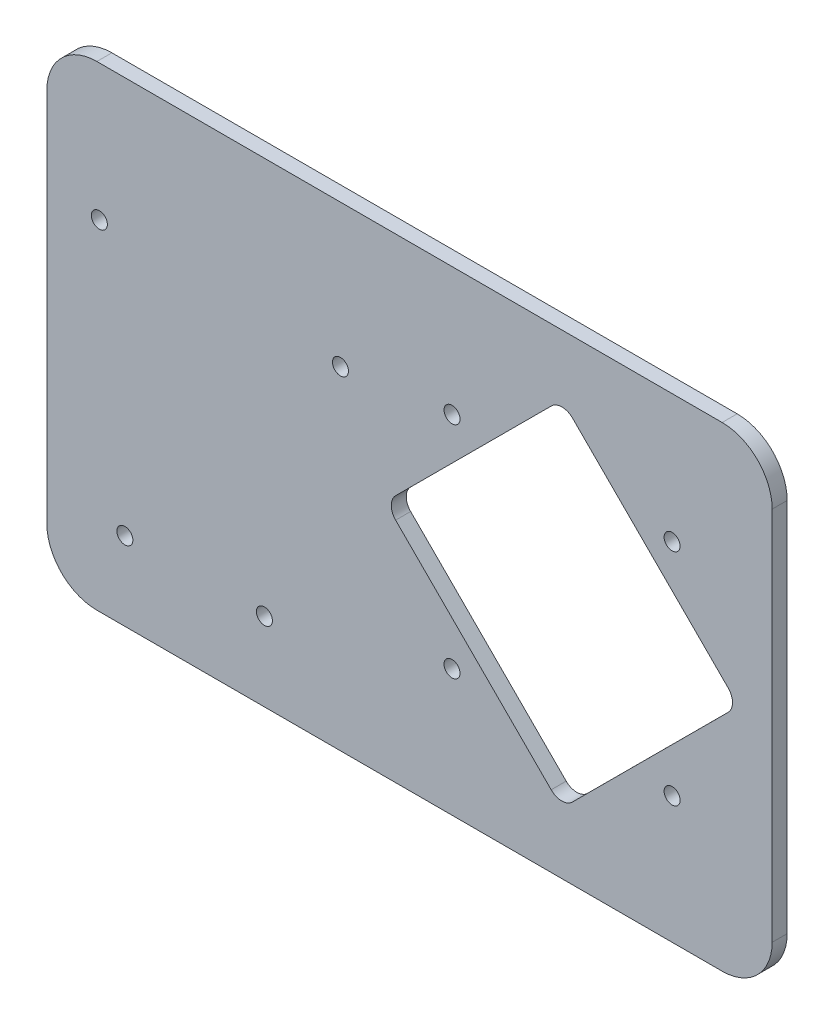
SolidWorks part; units mm, degrees
ref_plane "前视基准面" through (0, 0, 0) normal (0, 0, 1) x (1, 0, 0)
ref_plane "上视基准面" through (0, 0, 0) normal (0, 1, 0) x (1, 0, 0)
ref_plane "右视基准面" through (0, 0, 0) normal (1, 0, 0) x (0, 0, -1)
ref_plane "基准面4" through (0, 0, 0) normal (0, 0, -1) x (-1, 0, 0)
sketch "草图1" plane through (0, 0, 0) normal (0, 0, -1) x (-1, 0, 0)
  line L0 (-269.0741, 2.3138) -> (-144.0713, 2.3138)
  line L1 (-134.071, 12.314) -> (-134.071, 87.315)
  line L2 (-144.0713, 97.3152) -> (-269.0741, 97.3152)
  line L3 (-279.0743, 87.315) -> (-279.0743, 12.314)
  line L4 (-270.2724, 51.9704) -> (-239.1777, 83.1022)
  line L5 (-234.935, 83.1047) -> (-203.803, 52.0098)
  line L6 (-203.8005, 47.7671) -> (-234.8951, 16.6353)
  line L7 (-239.1378, 16.6328) -> (-270.2699, 47.7277)
  arc A0 (-144.0713, 2.3138) -> (-134.071, 12.314) centre (-144.0713, 12.314) ccw
  arc A1 (-134.071, 87.315) -> (-144.0713, 97.3152) centre (-144.0713, 87.315) ccw
  arc A2 (-269.0741, 97.3152) -> (-279.0743, 87.315) centre (-269.0741, 87.315) ccw
  arc A3 (-279.0743, 12.314) -> (-269.0741, 2.3138) centre (-269.0741, 12.314) ccw
  circle A4 centre (-144.5713, 70.1299) radius 1.6
  circle A5 centre (-192.7714, 68.8305) radius 1.6
  circle A6 centre (-149.6714, 18.0292) radius 1.6
  circle A7 centre (-215.0729, 71.6895) radius 1.6
  circle A8 centre (-259.0729, 71.6895) radius 1.6
  circle A9 centre (-259.0729, 27.6895) radius 1.6
  circle A10 centre (-215.0729, 27.6895) radius 1.6
  circle A11 centre (-177.572, 18.0292) radius 1.6
  arc A12 (-239.1777, 83.1022) -> (-234.935, 83.1047) centre (-237.0551, 80.9821) cw
  arc A13 (-203.803, 52.0098) -> (-203.8005, 47.7671) centre (-205.9231, 49.8872) cw
  arc A14 (-234.8951, 16.6353) -> (-239.1378, 16.6328) centre (-237.0177, 18.7554) cw
  arc A15 (-270.2699, 47.7277) -> (-270.2724, 51.9704) centre (-268.1498, 49.8503) cw
  dimension "D1" = 44
  dimension "D2" = 44
extrude "凸台-拉伸1" add sketch "草图1" against normal blind 3
sketch "草图2" plane through (0, 0, 0) normal (0, 0, -1) x (-1, 0, 0)
  text T0 "ZJUSRA" font "Engravers MT" height in points 20
extrude "切除-拉伸1" cut sketch "草图2" against normal blind 1
